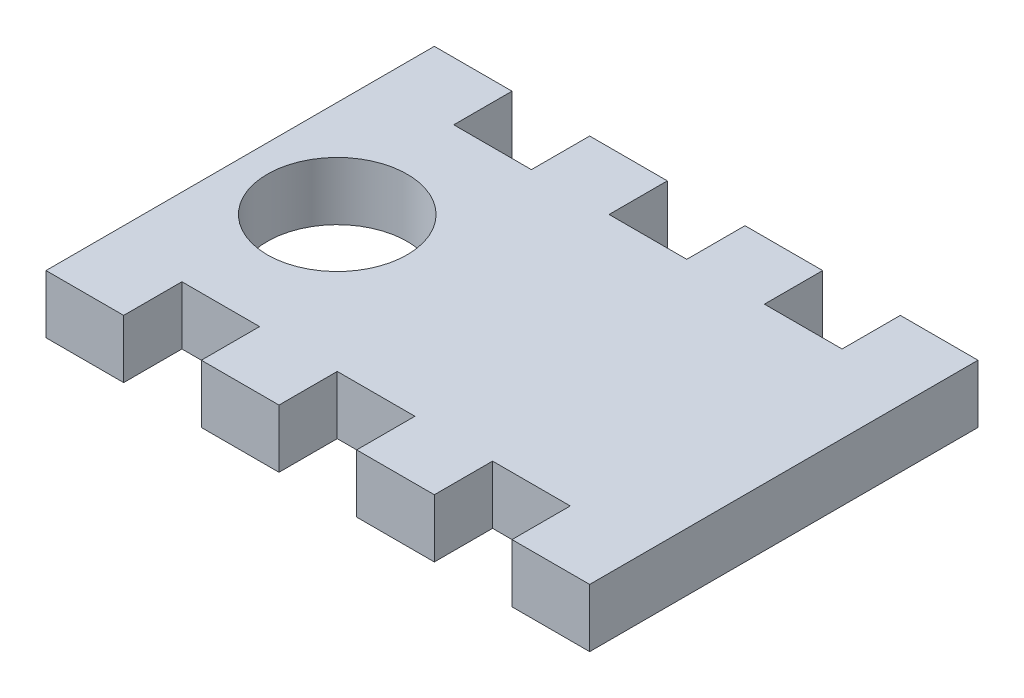
SolidWorks part; units mm, degrees
ref_plane "Alzado" through (0, 0, 0) normal (0, 0, 1) x (1, 0, 0)
ref_plane "Planta" through (0, 0, 0) normal (0, 1, 0) x (1, 0, 0)
ref_plane "Vista lateral" through (0, 0, 0) normal (1, 0, 0) x (0, 0, -1)
sketch "Croquis1" plane through (0, 0, 0) normal (0, 1, 0) x (1, 0, 0)
  line L1 (-14, -7) -> (14, -7)
  line L2 (-14, -7) -> (-14, 7)
  line L3 (-14, 7) -> (14, 7)
  line L4 (14, -7) -> (14, 7)
  line L5 (-14, -7) -> (14, 7) construction
  line L6 (-14, 7) -> (14, -7) construction
  line L22 (0, 0) -> (8.1519, 0) construction
  line L79 (-6, 7) -> (-6, 10)
  line L80 (-14, 7) -> (-10, 7)
  line L81 (-14, 7) -> (-14, 10)
  line L82 (-14, 10) -> (-10, 10)
  line L83 (-10, 7) -> (-10, 10)
  line L84 (-6, 7) -> (-2, 7)
  line L85 (-2, 7) -> (-2, 10)
  line L86 (-6, 10) -> (-2, 10)
  line L87 (2, 7) -> (2, 10)
  line L88 (2, 7) -> (6, 7)
  line L89 (6, 7) -> (6, 10)
  line L90 (2, 10) -> (6, 10)
  line L91 (10, 7) -> (10, 10)
  line L92 (10, 7) -> (14, 7)
  line L93 (14, 7) -> (14, 10)
  line L94 (10, 10) -> (14, 10)
  line L95 (10, -7) -> (14, -7)
  line L96 (14, -7) -> (14, -10)
  line L97 (10, -10) -> (14, -10)
  line L98 (10, -7) -> (10, -10)
  line L99 (2, -7) -> (6, -7)
  line L100 (6, -7) -> (6, -10)
  line L101 (2, -10) -> (6, -10)
  line L102 (2, -7) -> (2, -10)
  line L103 (-6, -7) -> (-2, -7)
  line L104 (-2, -7) -> (-2, -10)
  line L105 (-6, -10) -> (-2, -10)
  line L106 (-6, -7) -> (-6, -10)
  line L107 (-14, -10) -> (-10, -10)
  line L108 (-10, -7) -> (-10, -10)
  line L109 (-14, -7) -> (-10, -7)
  line L110 (-14, -7) -> (-14, -10)
  circle A0 centre (-9, 0) radius 3.6
  point P0 (0, 0)
  dimension "D16" = 7.2
  dimension "D1" = 28
  dimension "D2" = 14
  dimension "D3" = 4
  dimension "D4" = 3
  dimension "D5" = 4
  dimension "D15" = 23
extrude "Saliente-Extruir3" add sketch "Croquis1" along normal blind 3
